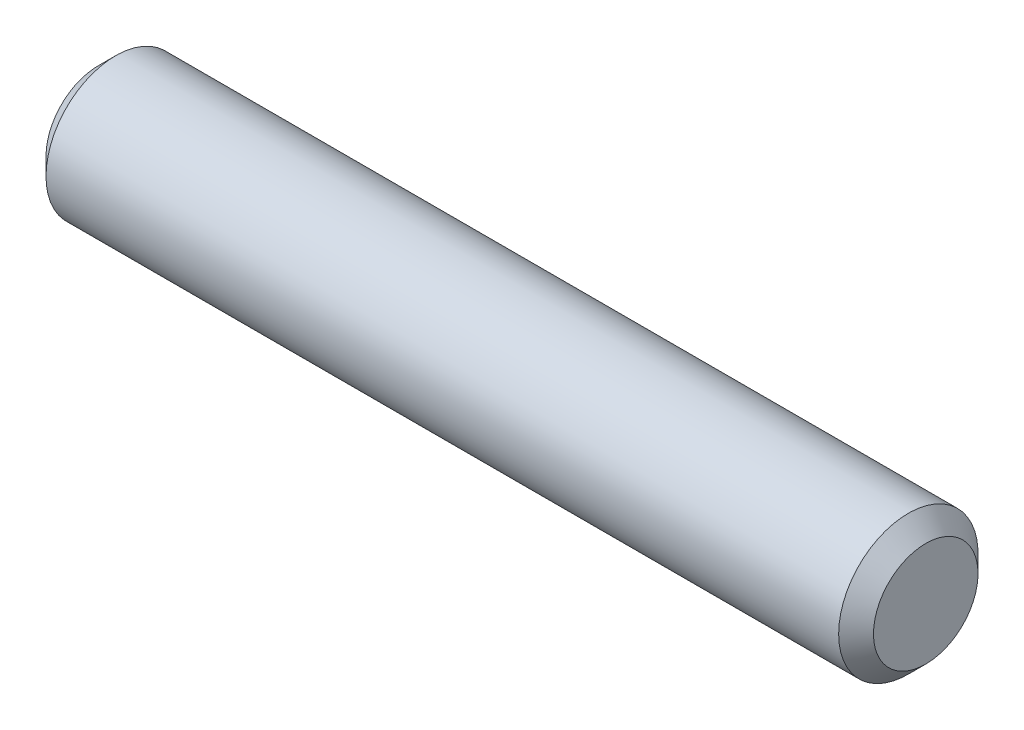
SolidWorks part; units mm, degrees
ref_plane "Front Plane" through (0, 0, 0) normal (0, 0, 1) x (1, 0, 0)
ref_plane "Top Plane" through (0, 0, 0) normal (0, 1, 0) x (1, 0, 0)
ref_plane "Right Plane" through (0, 0, 0) normal (1, 0, 0) x (0, 0, -1)
sketch "Sketch1" plane through (0, 0, 0) normal (0, 0, 1) x (1, 0, 0)
  line L0 (-23.75, 0) -> (23.75, 0) construction
  line L1 (-23.75, 0) -> (-23.75, 3)
  line L2 (-22.75, 4) -> (22.75, 4)
  line L3 (23.75, 3) -> (23.75, 0)
  line L4 (23.75, 0) -> (-23.75, 0)
  line L5 (-23.75, 3) -> (-22.75, 4)
  line L6 (22.75, 4) -> (23.75, 3)
  point P0 (23.75, 4)
  point P4 (0, 0)
  point P6 (-23.75, 4)
  dimension "D1" = 47.5
revolve "Revolve1" add sketch "Sketch1" angle 360 about L0
